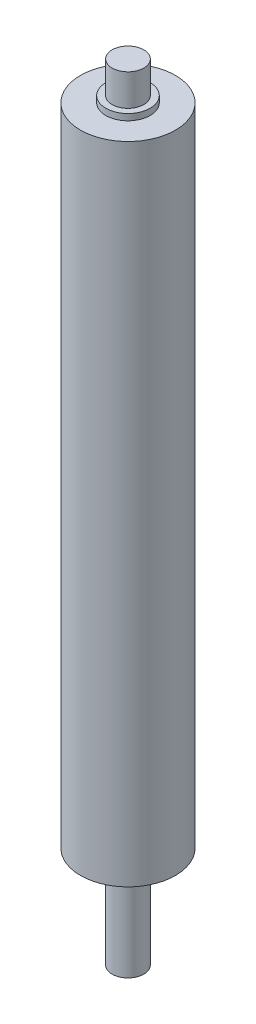
SolidWorks part; units mm, degrees
ref_plane "Front Plane" through (0, 0, 0) normal (0, 0, 1) x (1, 0, 0)
ref_plane "Top Plane" through (0, 0, 0) normal (0, 1, 0) x (1, 0, 0)
ref_plane "Right Plane" through (0, 0, 0) normal (1, 0, 0) x (0, 0, -1)
sketch "Sketch1" plane through (0, 0, 0) normal (0, 1, 0) x (1, 0, 0)
  circle A0 centre (0, 0) radius 7.5
  dimension "D1" = 15
extrude "Boss-Extrude1" add sketch "Sketch1" along normal blind 102
sketch "Sketch2" plane through (0, 0, 0) normal (0, -1, 0) x (1, 0, 0)
  circle A0 centre (0, 0) radius 3.5
  dimension "D1" = 7
extrude "Boss-Extrude2" add sketch "Sketch2" along normal blind 1
sketch "Sketch3" plane through (0, -1, 0) normal (0, -1, 0) x (1, 0, 0)
  circle A0 centre (0, 0) radius 2.5
  dimension "D1" = 5
extrude "Boss-Extrude3" add sketch "Sketch3" along normal blind 15
sketch "Sketch4" plane through (0, 102, 0) normal (0, 1, 0) x (1, 0, 0)
  circle A0 centre (0, 0) radius 3.5
  dimension "D1" = 7
extrude "Boss-Extrude4" add sketch "Sketch4" along normal blind 1
sketch "Sketch5" plane through (0, 103, 0) normal (0, 1, 0) x (1, 0, 0)
  circle A0 centre (0, 0) radius 2.5
  dimension "D1" = 5
extrude "Boss-Extrude5" add sketch "Sketch5" along normal blind 5
